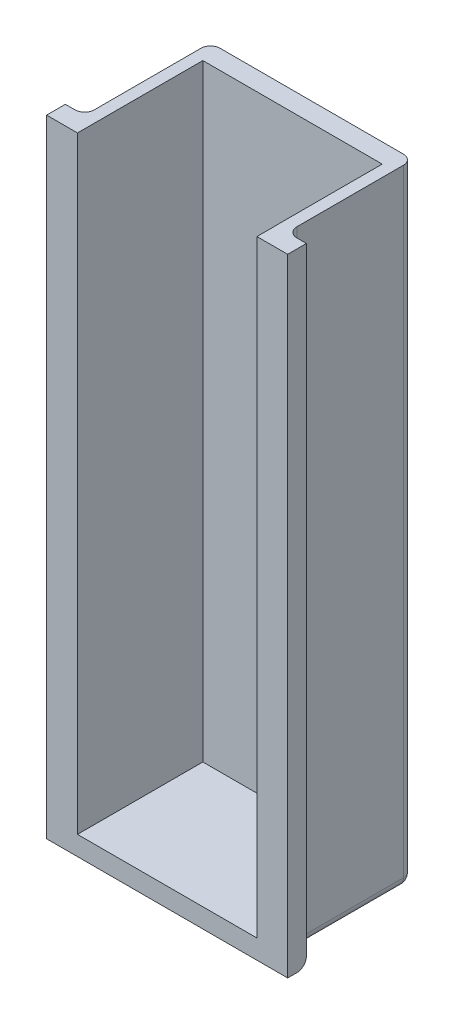
SolidWorks part; units mm, degrees
material "Plastique personnalisé"
ref_plane "Plan de face" through (0, 0, 0) normal (0, 0, 1) x (1, 0, 0)
ref_plane "Plan de dessus" through (0, 0, 0) normal (0, 1, 0) x (1, 0, 0)
ref_plane "Plan de droite" through (0, 0, 0) normal (1, 0, 0) x (0, 0, -1)
sketch "Esquisse1" plane through (0, 0, 0) normal (0, 0, 1) x (1, 0, 0)
  line L1 (-12.5, -32.5) -> (12.5, -32.5)
  line L2 (-12.5, -32.5) -> (-12.5, 32.5)
  line L3 (-12.5, 32.5) -> (12.5, 32.5)
  line L4 (12.5, -32.5) -> (12.5, 32.5)
  line L5 (-12.5, -32.5) -> (12.5, 32.5) construction
  line L6 (-12.5, 32.5) -> (12.5, -32.5) construction
  point P0 (0, 0)
  dimension "D1" = 25
  dimension "D2" = 65
extrude "Boss.-Extru.1" add sketch "Esquisse1" along normal blind 15
sketch "Esquisse2" plane through (0, 32.5, 0) normal (0, 1, 0) x (1, 0, 0)
  line L0 (-12.5, -15) -> (-12.5, -13.0028) construction
  line L1 (-12.5, -15) -> (-12.5, 0) construction
  line L2 (-12.5, -13.0554) -> (-10.5027, -13.0554) construction
  line L3 (-10.5027, -13.0554) -> (-10.5027, 0) construction
  line L4 (12.5, 0) -> (-12.5, 0) construction
  line L5 (0, 0) -> (0, -18.7369) construction
  line L6 (12.5, 0) -> (12.5, -13.0554)
  line L7 (-12.5, 0) -> (-10.5027, 0)
  line L8 (-12.5, 0) -> (-12.5, -13.0554)
  line L9 (-12.5, -13.0554) -> (-10.5027, -13.0554)
  line L10 (-10.5027, 0) -> (-10.5027, -13.0554)
  line L11 (12.5, -13.0554) -> (10.5027, -13.0554)
  line L12 (10.5027, 0) -> (10.5027, -13.0554)
  line L13 (12.5, 0) -> (10.5027, 0)
extrude "Enlèv. mat.-Extru.1" cut sketch "Esquisse2" against normal through all both and the other way through all
sketch "Esquisse3" plane through (0, 32.5, 0) normal (0, 1, 0) x (1, 0, 0)
  line L0 (-9.3, -15) -> (-9.3, -1.9977) construction
  line L1 (12.5, -15) -> (-12.5, -15) construction
  line L2 (0, -15) -> (0, 6.1939) construction
  line L3 (-12.5, -15) -> (12.5, -15) construction
  line L4 (9.3, -15) -> (9.3, -1.9977) construction
  line L6 (-9.3, -1.9977) -> (9.3, -1.9977)
  line L7 (-9.3, -1.9977) -> (-9.3, -12.9625)
  line L8 (-9.3, -12.9625) -> (9.3, -12.9625)
  line L9 (9.3, -1.9977) -> (9.3, -12.9625)
extrude "Enlèv. mat.-Extru.2" cut sketch "Esquisse3" against normal blind 63
sketch "Esquisse4" plane through (0, 32.5, 0) normal (0, 1, 0) x (1, 0, 0)
  line L0 (12.5, -15) -> (-12.5, -15) construction
  line L1 (-9.3, -12.9625) -> (9.3106, -12.9625)
  line L2 (-9.3, -12.9625) -> (-9.3, -15)
  line L3 (-9.3, -15) -> (9.3106, -15)
  line L4 (9.3106, -12.9625) -> (9.3106, -15)
extrude "Enlèv. mat.-Extru.3" cut sketch "Esquisse4" against normal up to surface (63 mm away) up to face at (0, -30.5, 7.4801)
fillet "Congé1" radius 1 9 edges at (-11.5013, -32.5, 13.0554) (11.5013, -32.5, 13.0554) (-10.5027, 0, 13.0554) (-10.5027, -32.5, 6.5277) (10.5027, 0, 13.0554) (10.5027, -32.5, 6.5277) (0, -32.5, 0) (-10.5027, 0, 0) (10.5027, 0, 0)
